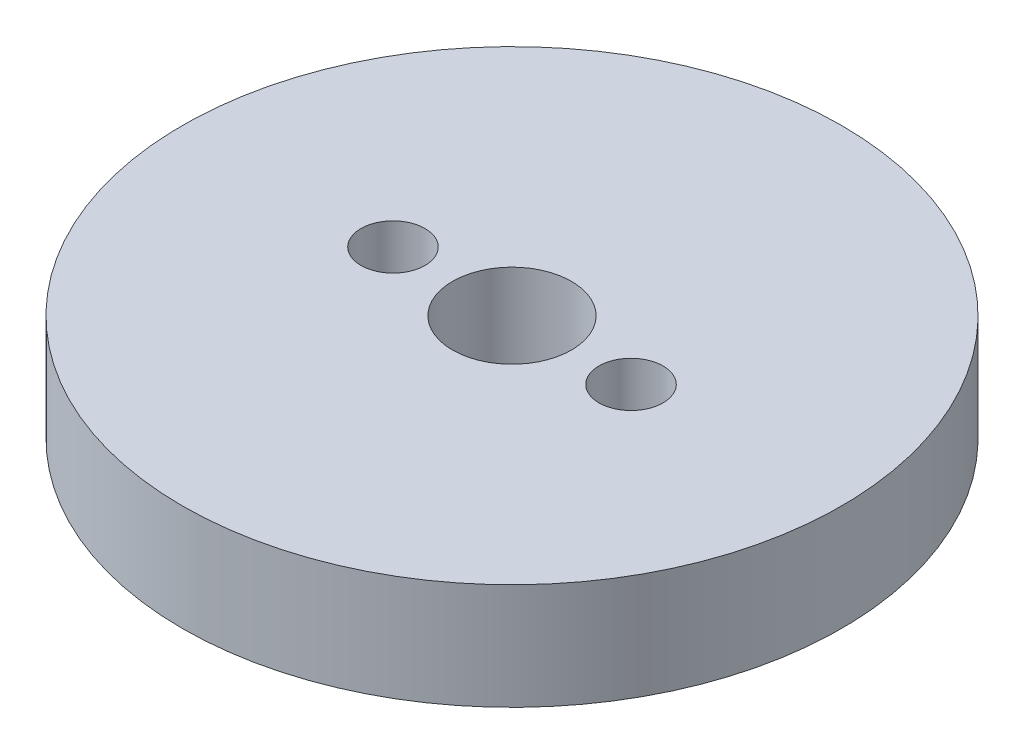
SolidWorks part; units mm, degrees
material "MC901"
ref_plane "正面" through (0, 0, 0) normal (0, 0, 1) x (1, 0, 0)
ref_plane "平面" through (0, 0, 0) normal (0, 1, 0) x (1, 0, 0)
ref_plane "右側面" through (0, 0, 0) normal (1, 0, 0) x (0, 0, -1)
sketch "ｽｹｯﾁ1" plane through (0, 0, 0) normal (0, 1, 0) x (1, 0, 0)
  line L0 (0, 3.25) -> (0, 0) construction
  line L1 (0, 0) -> (6.5, 0) construction
  circle A0 centre (0, 0) radius 18
  circle A1 centre (0, 0) radius 3.25
  circle A2 centre (6.5, 0) radius 1.75
  circle A3 centre (-6.5, 0) radius 1.75
  dimension "D1" = 36
  dimension "D2" = 6.5
  dimension "D3" = 3.5
  dimension "D4" = 13
extrude "ﾎﾞｽ - 押し出し1" add sketch "ｽｹｯﾁ1" along normal blind 5.8
